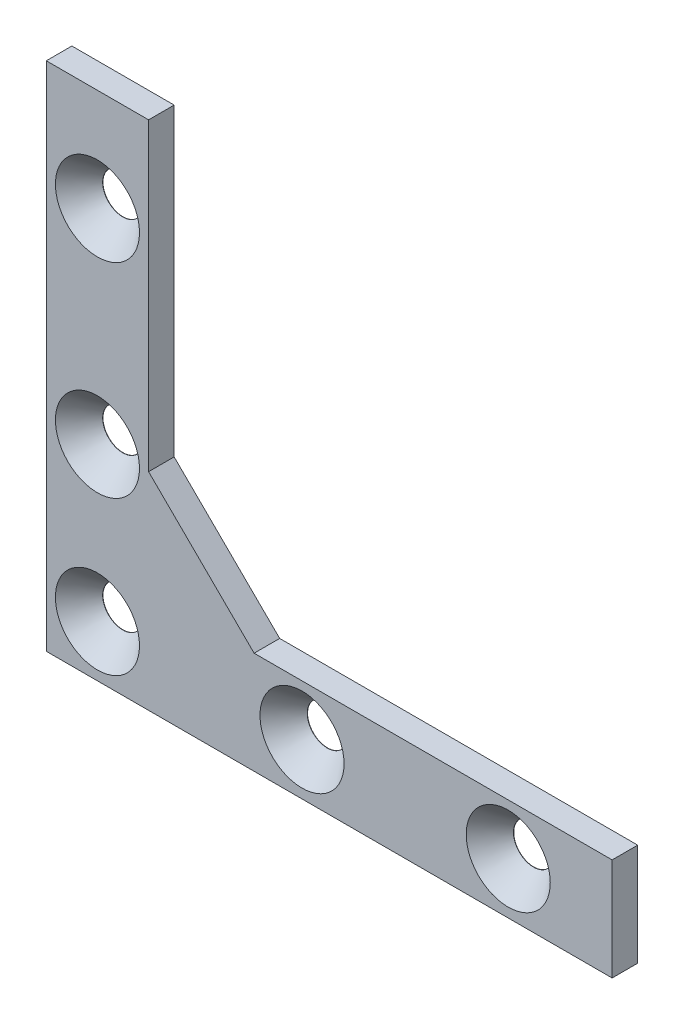
SolidWorks part; units mm, degrees
ref_plane "Front Plane" through (0, 0, 0) normal (0, 0, 1) x (1, 0, 0)
ref_plane "Top Plane" through (0, 0, 0) normal (0, 1, 0) x (1, 0, 0)
ref_plane "Right Plane" through (0, 0, 0) normal (1, 0, 0) x (0, 0, -1)
sketch "Sketch1" plane through (0, 0, 0) normal (0, 0, 1) x (1, 0, 0)
  line L0 (-260.35, 0) -> (-273.4534, 0)
  line L1 (-273.4534, 0) -> (-273.4534, 63.5)
  line L2 (-273.4534, 63.5) -> (-260.7534, 63.5)
  line L4 (-260.35, 0) -> (-203.2, 0)
  line L6 (-203.2, 0) -> (-203.2, 12.7)
  line L7 (-254, 12.7) -> (254, 12.7) construction
  line L8 (-203.2, 12.7) -> (-247.65, 12.7)
  line L9 (-247.65, 12.7) -> (-260.7534, 25.666)
  line L10 (-260.7534, 25.666) -> (-260.7534, 63.5)
  point P2 (0, 0)
  point P9 (0, 0)
  point P10 (0, 0)
  point P13 (0, 0)
  dimension "D1" = 63.5
  dimension "D2" = 12.7
  dimension "D3" = 57.15
  dimension "D4" = 44.45
  dimension "D5" = 12.7
extrude "Boss-Extrude1" add sketch "Sketch1" along normal blind 3.175
sketch "Sketch2" plane through (0, 0, 3.175) normal (0, 0, 1) x (1, 0, 0)
  line L0 (-267.1034, 63.5) -> (-267.1034, 50.8) construction
  line L1 (-260.7534, 63.5) -> (-273.4534, 63.5) construction
  line L2 (-267.1034, 50.8) -> (-267.1034, 25.4382) construction
  line L3 (-267.1034, 6.3882) -> (-241.7034, 6.3882) construction
  line L4 (-267.1034, 25.4382) -> (-267.1034, 6.3882) construction
  line L5 (-241.7034, 6.3882) -> (-216.1017, 6.3882) construction
  line L6 (-203.2, 6.35) -> (-216.1017, 6.3882) construction
  line L7 (-203.2, 0) -> (-203.2, 12.7) construction
  dimension "D1" = 19.05
  dimension "D2" = 25.4
hole_wizard "#10 Clearance Hole1" positions "Sketch3" profile "Sketch4" hole size "#10" standard "ANSI Inch" end condition through all
sketch "Sketch3" plane through (0, 0, 3.175) normal (0, 0, 1) x (1, 0, 0)
  point P0 (-267.1034, 6.3882)
  point P3 (-267.1034, 25.4382)
  point P6 (-267.1034, 50.8)
  point P9 (-241.7034, 6.3882)
  point P12 (-216.1017, 6.3882)
sketch "Sketch4" plane through (-267.1034, 6.3882, 3.175) normal (1, 0, 0) x (0, -1, 0)
  line L0 (0, 0) -> (0, 3.175)
  line L1 (0, 3.175) -> (2.4892, 3.175)
  line L2 (2.4892, 3.175) -> (2.4892, 3.1411)
  line L3 (2.4892, 3.1411) -> (5.2197, 0)
  line L5 (5.2197, 0) -> (0, 0)
  line L6 (-2.4892, 3.1411) -> (-5.2197, 0) construction
  line L11 (0, -6.35) -> (0, 107.95) construction
  dimension "Thru Hole Dia." = 4.9784
  dimension "Thru Hole Depth" = 3.175
  dimension "Near C'Sink Dia." = 10.4394
  dimension "Near C'Sink Angle" = 82
